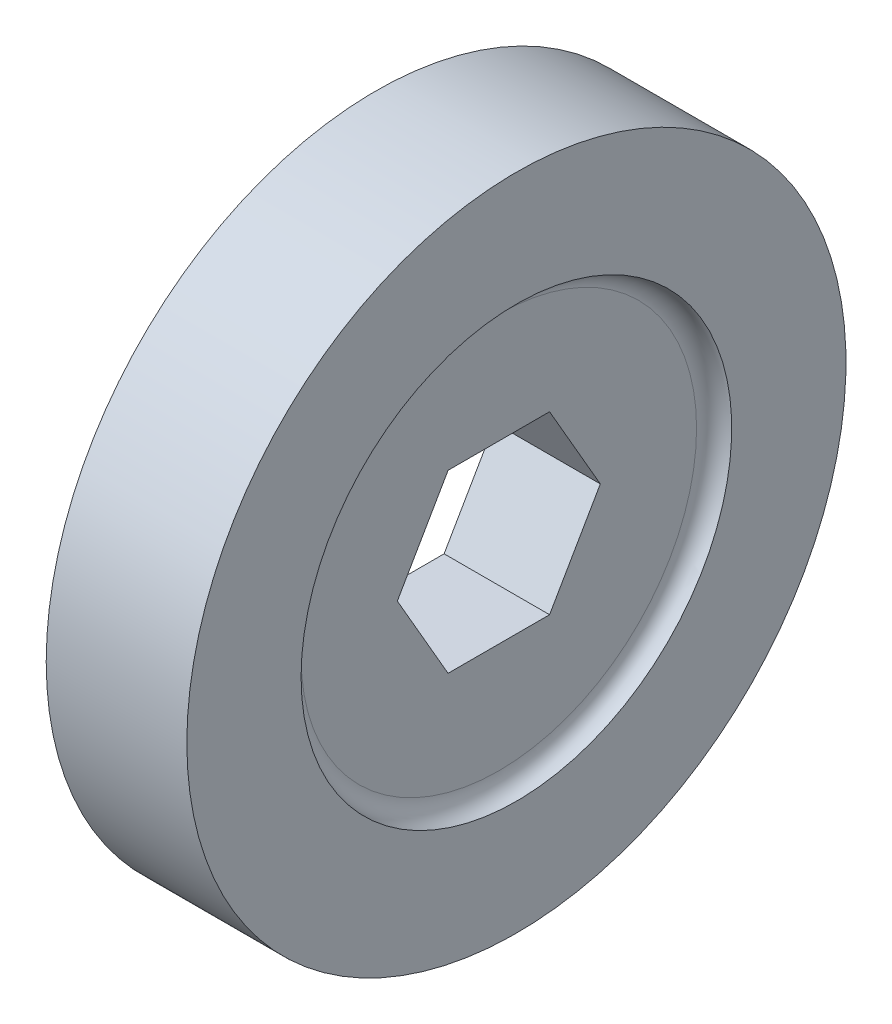
SolidWorks part; units mm, degrees
ref_plane "Front Plane" through (0, 0, 0) normal (0, 0, 1) x (1, 0, 0)
ref_plane "Top Plane" through (0, 0, 0) normal (0, 1, 0) x (1, 0, 0)
ref_plane "Right Plane" through (0, 0, 0) normal (1, 0, 0) x (0, 0, -1)
sketch "Sketch2" plane through (0, 0, 0) normal (0, 0, 1) x (1, 0, 0)
  line L0 (0, 0) -> (0, 23.8125) construction
  line L1 (-5.08, 23.8125) -> (5.08, 23.8125)
  line L2 (5.08, 23.8125) -> (5.08, 15.5575)
  line L3 (3.81, 14.2875) -> (3.81, 0)
  line L4 (-3.81, 14.2875) -> (-3.81, 0)
  line L5 (-5.08, 23.8125) -> (-5.08, 15.5575)
  line L6 (-3.81, 0) -> (3.81, 0)
  line L7 (-6.8694, 0) -> (10.1347, 0) construction
  arc A0 (5.08, 15.5575) -> (3.81, 14.2875) centre (5.08, 14.2875) ccw
  arc A1 (-5.08, 15.5575) -> (-3.81, 14.2875) centre (-5.08, 14.2875) cw
  point P6 (0, 23.8125)
  dimension "D2" = 7.62
  dimension "D1" = 23.8125
  dimension "D3" = 10.16
  dimension "D4" = 15.5575
revolve "Revolve1" add sketch "Sketch2" angle 360 about L7
sketch "Sketch3" plane through (3.81, 0, 0) normal (1, 0, 0) x (0, 0, -1)
  line L1 (7.3323, 0) -> (3.6662, 6.35)
  line L2 (3.6662, 6.35) -> (-3.6662, 6.35)
  line L3 (-3.6662, 6.35) -> (-7.3323, 0)
  line L4 (-7.3323, 0) -> (-3.6662, -6.35)
  line L5 (-3.6662, -6.35) -> (3.6662, -6.35)
  line L6 (3.6662, -6.35) -> (7.3323, 0)
  circle A0 centre (0, 0) radius 6.35 construction
  dimension "D1" = 12.7
extrude "Cut-Extrude1" cut sketch "Sketch3" against normal up to next
